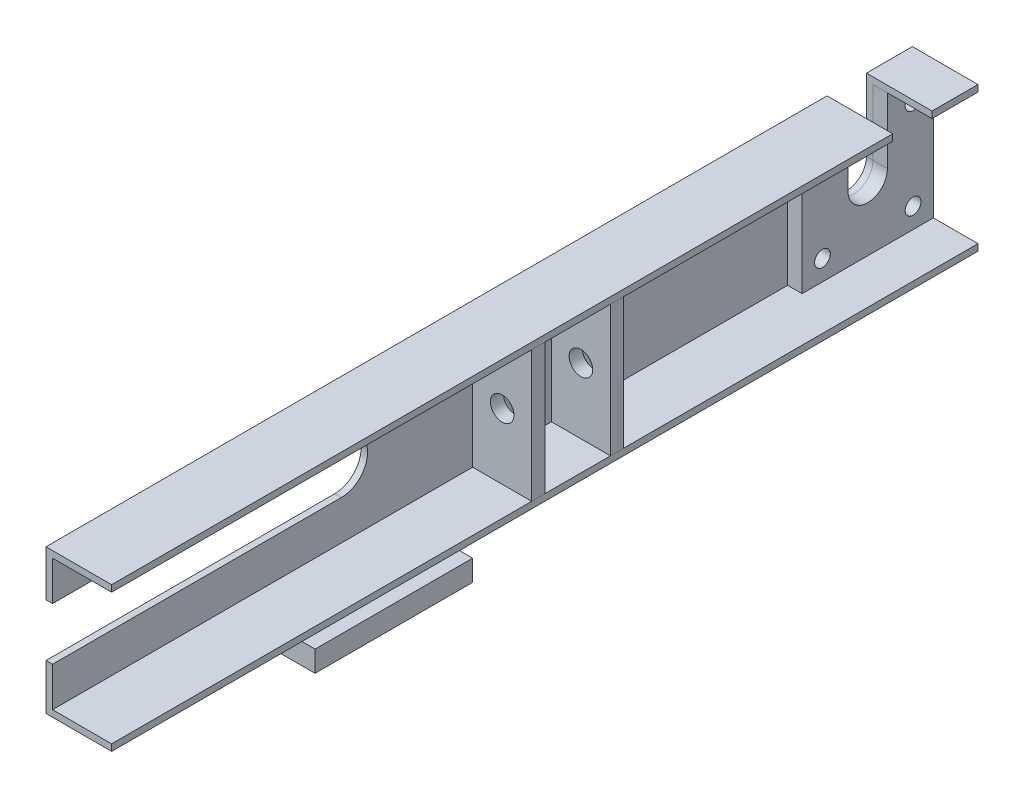
SolidWorks part; units mm, degrees
ref_plane "Front Plane" through (0, 0, 0) normal (0, 0, 1) x (1, 0, 0)
ref_plane "Top Plane" through (0, 0, 0) normal (0, 1, 0) x (1, 0, 0)
ref_plane "Right Plane" through (0, 0, 0) normal (1, 0, 0) x (0, 0, -1)
sketch "Sketch1" plane through (0, 0, 0) normal (1, 0, 0) x (0, 0, -1)
  line L0 (-330, 0) -> (330, 0)
  point P5 (0, 0)
  dimension "D1" = 660
other "C channel 100 X 10(1)"
ref_plane "Plane1" through (0, 0, 330) normal (0, 0, -1) x (0, 1, 0)
sketch "Sketch11" plane through (0, 0, 330) normal (0, 0, -1) x (0, 1, 0)
  line L0 (-55, 0) -> (55, 0)
  line L1 (55, 0) -> (55, 50)
  line L2 (55, 50) -> (50, 50)
  line L3 (50, 50) -> (50, 5)
  line L4 (50, 5) -> (-50, 5)
  line L5 (0, 5) -> (0, 0) construction
  line L6 (-50, 50) -> (-50, 5)
  line L7 (-55, 50) -> (-50, 50)
  line L8 (-55, 0) -> (-55, 50)
  dimension "D4" = 5
  dimension "D2" = 50
  dimension "D1" = 110
  dimension "D3" = 5
sketch "Sketch12" plane through (0, -50, 0) normal (0, 1, 0) x (1, 0, 0)
  line L0 (50, 330) -> (50, -330) construction
  line L1 (5, 0) -> (50, 0)
  line L2 (5, 0) -> (5, -10)
  line L3 (5, -10) -> (50, -10)
  line L4 (50, 0) -> (50, -10)
  line L5 (5, 330) -> (5, -330) construction
  line L6 (0, 330) -> (50, 330) construction
  line L8 (50, 50) -> (5, 50)
  line L9 (50, 50) -> (50, 60)
  line L10 (50, 60) -> (5, 60)
  line L11 (5, 50) -> (5, 60)
  dimension "D1" = 10
  dimension "D2" = 340
  dimension "D3" = 280
extrude "Boss-Extrude1" add sketch "Sketch12" along normal up to next separate body
sketch "Sketch13" plane through (5, 0, 0) normal (1, 0, 0) x (0, 0, -1)
  line L0 (-330, 20) -> (-110, 20)
  line L1 (-330, 50) -> (-330, -50) construction
  line L2 (-330, -20) -> (-110, -20)
  line L3 (-330, 0) -> (-106.1115, 0) construction
  line L4 (-330, 20) -> (-330, -20)
  arc A0 (-110, 20) -> (-110, -20) centre (-110, 0) cw
  dimension "D1" = 40
  dimension "D2" = 240
extrude "Cut-Extrude1" cut sketch "Sketch13" against normal up to next (5 mm away)
sketch "Sketch17" plane through (5, 0, 0) normal (1, 0, 0) x (0, 0, -1)
  line L0 (330, 50) -> (-330, 50) construction
  line L1 (230, 50) -> (330, 50)
  line L2 (230, 50) -> (230, -50)
  line L3 (230, -50) -> (330, -50)
  line L4 (330, 50) -> (330, -50)
  line L5 (330, 50) -> (330, -50) construction
  line L6 (330, -50) -> (-330, -50) construction
  dimension "D1" = 100
extrude "Boss-Extrude3" add sketch "Sketch17" along normal blind 11 separate body
sketch "Sketch15" plane through (0, -55, 0) normal (0, -1, 0) x (1, 0, 0)
  line L0 (50, -330) -> (0, -330) construction
  line L1 (-5, 185) -> (60, 185)
  line L2 (-5, 185) -> (-5, 65)
  line L3 (-5, 65) -> (60, 65)
  line L4 (60, 185) -> (60, 65)
  line L5 (0, -330) -> (0, 330) construction
  dimension "D1" = 395
  dimension "D2" = 120
  dimension "D3" = 65
  dimension "D4" = 5
extrude "Boss-Extrude2" add sketch "Sketch15" along normal blind 16 separate body
sketch "Sketch14" plane through (5, 0, 0) normal (1, 0, 0) x (0, 0, -1)
  line L0 (265, 55) -> (265, 0)
  line L1 (330, 55) -> (-330, 55) construction
  line L2 (330, 50) -> (330, -50) construction
  line L3 (295, 0) -> (295, 55)
  line L4 (265, 55) -> (295, 55)
  arc A0 (265, 0) -> (295, 0) centre (280, 0) ccw
  point P5 (280, -15)
  dimension "D1" = 30
  dimension "D2" = 35
  dimension "D3" = 70
extrude "Cut-Extrude2" cut sketch "Sketch14" against normal through all both and the other way through all
sketch "Sketch18" [suppressed] plane through (5, 0, 0) normal (1, 0, 0) x (0, 0, -1)
  line L0 (265, -55) -> (265, 0)
  line L1 (330, -55) -> (-330, -55) construction
  line L2 (265, 0) -> (295, 0) construction
  line L3 (295, 0) -> (295, -55)
  line L4 (330, -50) -> (330, 50) construction
  line L8 (265, -55) -> (295, -55)
  arc A0 (265, 0) -> (295, 0) centre (280, 0) cw
  dimension "D1" = 30
  dimension "D2" = 35
extrude "Cut-Extrude3" [suppressed] cut sketch "Sketch18" against normal through all both and the other way through all
sketch "Sketch19" plane through (30, 0, 0) normal (1, 0, 0) x (0, 0, -1)
  circle A0 centre (314.5, -34.5) radius 6 construction
  circle A1 centre (245.5, -34.5) radius 6 construction
  circle A2 centre (314.5, 34.5) radius 6 construction
  circle A3 centre (245.5, 34.5) radius 6 construction
  circle A4 centre (314.5, -34.5) radius 6
  circle A5 centre (245.5, -34.5) radius 6
  circle A6 centre (314.5, 34.5) radius 6
  circle A7 centre (245.5, 34.5) radius 6
extrude "Cut-Extrude4" cut sketch "Sketch19" against normal up to vertex (25 mm away) up to point (5, 50, -330)
sketch "Sketch20" plane through (0, 0, 0) normal (-1, 0, 0) x (0, 0, 1)
  circle A0 centre (-25, 30) radius 5 construction
  circle A1 centre (-120, 30) radius 5 construction
  circle A2 centre (-25, 30) radius 5
  circle A3 centre (-120, 30) radius 5
extrude "Cut-Extrude5" cut sketch "Sketch20" against normal through all
sketch "Sketch21" [suppressed] plane through (0, 0, 0) normal (-1, 0, 0) x (0, 0, 1)
  circle A0 centre (-25, -30) radius 5 construction
  circle A1 centre (-120, -30) radius 5 construction
  circle A2 centre (-25, -30) radius 5
  circle A3 centre (-120, -30) radius 5
extrude "Cut-Extrude6" [suppressed] cut sketch "Sketch21" against normal through all
sketch "Sketch22" plane through (0, 0, 10) normal (0, 0, 1) x (1, 0, 0)
  line L0 (5, 50) -> (50, 50) construction
  circle A0 centre (27.5, 0) radius 9
  point P5 (27.5, 50)
  dimension "D1" = 18
extrude "Cut-Extrude7" cut sketch "Sketch22" against normal up to surface (70 mm away) up to face at (27.5, 0, -60)
